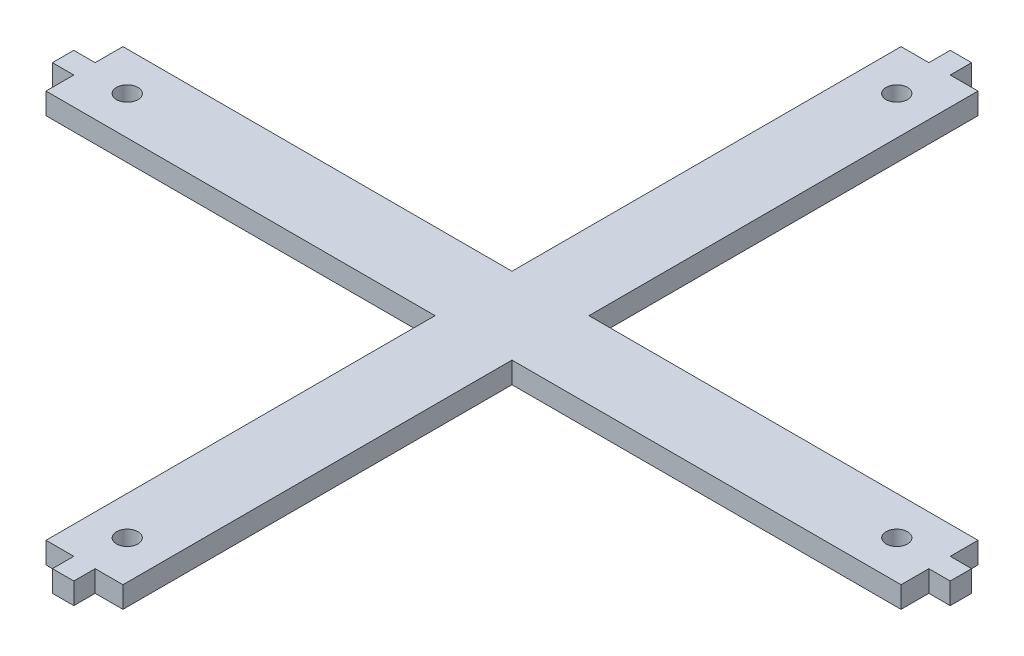
SolidWorks part; units mm, degrees
ref_plane "Front" through (0, 0, 0) normal (0, 0, 1) x (1, 0, 0)
ref_plane "Top" through (0, 0, 0) normal (0, 1, 0) x (1, 0, 0)
ref_plane "Right" through (0, 0, 0) normal (1, 0, 0) x (0, 0, -1)
sketch "Sketch1" plane through (0, 0, 0) normal (0, 1, 0) x (1, 0, 0)
  line L0 (-127, -3.175) -> (-127, -11.43)
  line L1 (-127, 11.43) -> (-11.43, 11.43)
  line L2 (-127, 11.43) -> (-127, 3.175)
  line L3 (-127, -11.43) -> (-11.43, -11.43)
  line L4 (127, 11.43) -> (127, 3.175)
  line L5 (11.43, -11.43) -> (127, -11.43)
  line L6 (-127, -11.43) -> (-11.43, -1.0287) construction
  line L7 (-133.35, 3.175) -> (-127, 3.175)
  line L8 (-133.35, 3.175) -> (-133.35, -3.175)
  line L9 (-133.35, -3.175) -> (-127, -3.175)
  line L11 (127, -3.175) -> (127, -11.43)
  line L12 (-133.35, -3.175) -> (-127, 0) construction
  line L13 (127, 3.175) -> (133.35, 3.175)
  line L15 (127, -3.175) -> (133.35, -3.175)
  line L16 (133.35, 3.175) -> (133.35, -3.175)
  line L17 (3.175, 127) -> (11.43, 127)
  line L18 (-11.43, 127) -> (-3.175, 127)
  line L19 (-11.43, 127) -> (-11.43, 11.43)
  line L20 (-11.43, -127) -> (-3.175, -127)
  line L21 (11.43, 127) -> (11.43, 11.43)
  line L22 (3.175, -127) -> (11.43, -127)
  line L23 (-11.43, -127) -> (-0.9797, -11.43) construction
  line L25 (-3.175, 127) -> (-3.175, 133.35)
  line L26 (-3.175, 133.35) -> (3.175, 133.35)
  line L27 (3.175, 127) -> (3.175, 133.35)
  line L28 (0, 127) -> (3.175, 133.35) construction
  line L29 (-3.175, 133.35) -> (0, 127) construction
  line L31 (-3.175, -127) -> (-3.175, -133.35)
  line L32 (-3.175, -133.35) -> (3.175, -133.35)
  line L33 (3.175, -127) -> (3.175, -133.35)
  line L38 (11.43, 11.43) -> (127, 11.43)
  line L40 (11.43, -11.43) -> (11.43, -127)
  line L41 (0.9797, -5.08) -> (11.43, -127) construction
  line L43 (-11.43, -11.43) -> (-11.43, -127)
  circle A0 centre (-114.3, 0) radius 3.175
  circle A1 centre (114.3, 0) radius 3.175
  circle A2 centre (0, 114.3) radius 3.175
  circle A3 centre (0, -114.3) radius 3.175
  point P0 (0, 0)
  point P6 (-127, 0)
  point P7 (127, 0)
  point P21 (0.6231, 6.2951)
  point P26 (0, 127)
  point P31 (0, -133.35)
  point P42 (7.3025, 127)
  dimension "D4" = 6.35
  dimension "D6" = 12.7
  dimension "D7" = 6.35
  dimension "D8" = 12.7
  dimension "D12" = 6.35
  dimension "D13" = 12.7
  dimension "D15" = 6.35
  dimension "D16" = 12.7
  dimension "D1" = 254
  dimension "D2" = 22.86
  dimension "D3" = 6.35
  dimension "D5" = 6.35
  dimension "D9" = 254
  dimension "D10" = 22.86
  dimension "D11" = 6.35
  dimension "D14" = 6.35
  dimension "D17" = 22.86
  dimension "D18" = 6.35
  dimension "D19" = 6.35
  dimension "D20" = 115.57
  dimension "D21" = 115.57
extrude "Boss-Extrude1" add sketch "Sketch1" along normal blind 6.35
